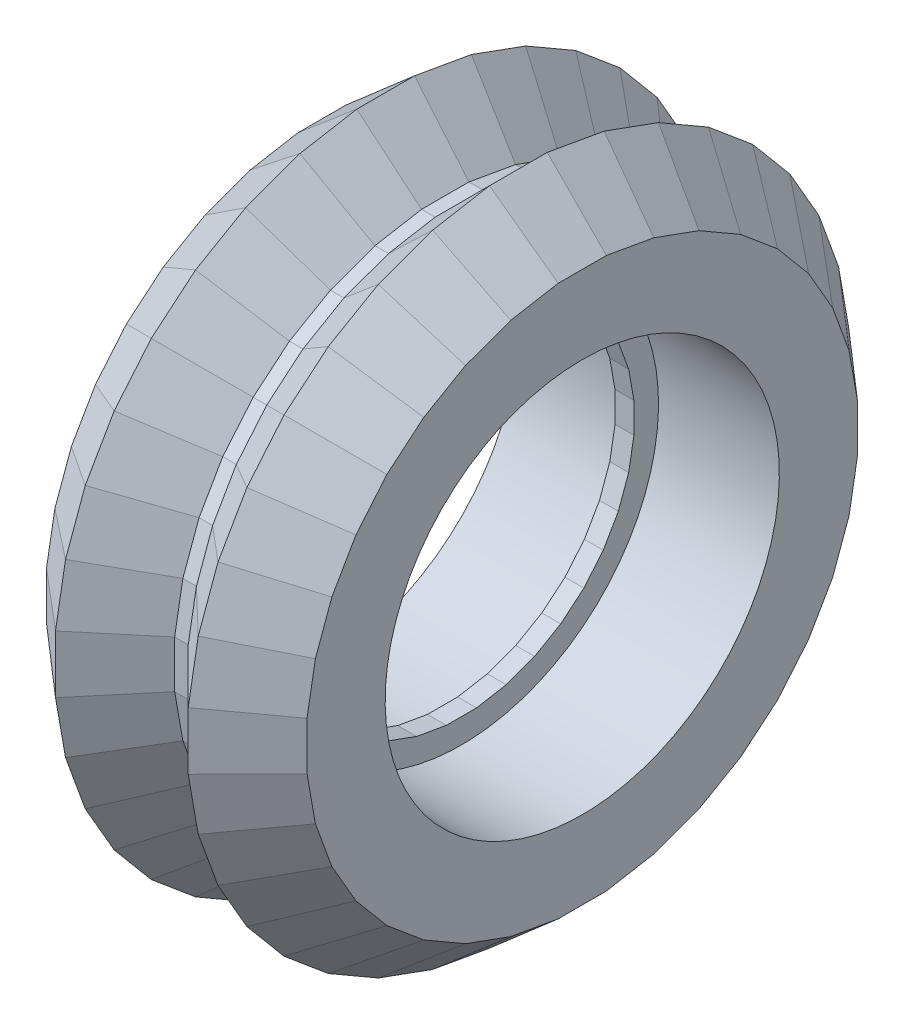
SolidWorks part; units mm, degrees
material "Chrome Stainless Steel"
ref_plane "Front Plane" through (0, 0, 0) normal (0, 0, 1) x (1, 0, 0)
ref_plane "Top Plane" through (0, 0, 0) normal (0, 1, 0) x (1, 0, 0)
ref_plane "Right Plane" through (0, 0, 0) normal (1, 0, 0) x (0, 0, -1)
sketch "Sketch1" plane through (0, 0, 0) normal (0, 0, 1) x (1, 0, 0)
  line L0 (-0.275, 10.9817) -> (0.275, 10.9817)
  line L1 (0.3833, 7) -> (0.3833, 7.5)
  line L2 (0.3833, 7.5) -> (5.0033, 7.5)
  line L3 (5.0033, 7.5) -> (5.2863, 7.783)
  line L4 (5.2863, 7.783) -> (5.2863, 11.17)
  line L5 (0.275, 10.9817) -> (2.6933, 13.4)
  line L6 (-0.3833, 7) -> (0.3833, 7)
  line L7 (-2.6933, 13.4) -> (-2.6933, 7.5) construction
  line L8 (-2.6933, 13.4) -> (-5.2863, 11.17)
  line L9 (2.6933, 13.4) -> (2.6933, 7.5) construction
  line L10 (0, 7) -> (0, 10.9817) construction
  line L11 (0, 7) -> (0, 0) construction
  line L12 (0, 0) -> (-5, 0) construction
  line L13 (-0.275, 10.9817) -> (-2.6933, 13.4)
  line L14 (-5.2863, 7.783) -> (-5.2863, 11.17)
  line L15 (2.6933, 13.4) -> (5.2863, 11.17)
  line L16 (-5.0033, 7.5) -> (-5.2863, 7.783)
  line L17 (-0.3833, 7.5) -> (-5.0033, 7.5)
  line L18 (-0.3833, 7) -> (-0.3833, 7.5)
  dimension "D2" = 90
  dimension "D3" = 3.42
  dimension "D4" = 7.5
  dimension "D5" = 0.275
  dimension "D6" = 4.62
  dimension "D7" = 135
  dimension "D8" = 0.4002
  dimension "D9" = 13.4
  dimension "D10" = 7
  dimension "D11" = 5
sketch "Sketch2" plane through (0, 0, 0) normal (1, 0, 0) x (0, 0, -1)
  line L0 (3.1177, -11.6354) -> (5.0908, -10.9172)
  line L1 (-8.5177, -8.5177) -> (-6.9092, -9.8674)
  line L2 (-6.9092, -9.8674) -> (-5.0908, -10.9172)
  line L3 (-5.0908, -10.9172) -> (-3.1177, -11.6354)
  line L4 (-3.1177, -11.6354) -> (-1.0499, -12)
  line L5 (-1.0499, -12) -> (1.0499, -12)
  line L6 (1.0499, -12) -> (3.1177, -11.6354)
  line L7 (5.0908, -10.9172) -> (6.9092, -9.8674)
  line L8 (6.9092, -9.8674) -> (8.5177, -8.5177)
  line L9 (8.5177, -8.5177) -> (9.8674, -6.9092)
  line L10 (9.8674, -6.9092) -> (10.9172, -5.0908)
  line L11 (10.9172, -5.0908) -> (11.6354, -3.1177)
  line L12 (11.6354, -3.1177) -> (12, -1.0499)
  line L13 (12, -1.0499) -> (12, 1.0499)
  line L14 (12, 1.0499) -> (11.6354, 3.1177)
  line L15 (11.6354, 3.1177) -> (10.9172, 5.0908)
  line L16 (10.9172, 5.0908) -> (9.8674, 6.9092)
  line L17 (9.8674, 6.9092) -> (8.5177, 8.5177)
  line L18 (8.5177, 8.5177) -> (6.9092, 9.8674)
  line L19 (6.9092, 9.8674) -> (5.0908, 10.9172)
  line L20 (5.0908, 10.9172) -> (3.1177, 11.6354)
  line L21 (3.1177, 11.6354) -> (1.0499, 12)
  line L22 (1.0499, 12) -> (-1.0499, 12)
  line L23 (-1.0499, 12) -> (-3.1177, 11.6354)
  line L24 (-3.1177, 11.6354) -> (-5.0908, 10.9172)
  line L25 (-5.0908, 10.9172) -> (-6.9092, 9.8674)
  line L26 (-6.9092, 9.8674) -> (-8.5177, 8.5177)
  line L27 (-8.5177, 8.5177) -> (-9.8674, 6.9092)
  line L28 (-9.8674, 6.9092) -> (-10.9172, 5.0908)
  line L29 (-10.9172, 5.0908) -> (-11.6354, 3.1177)
  line L30 (-11.6354, 3.1177) -> (-12, 1.0499)
  line L31 (-12, 1.0499) -> (-12, -1.0499)
  line L32 (-12, -1.0499) -> (-11.6354, -3.1177)
  line L33 (-11.6354, -3.1177) -> (-10.9172, -5.0908)
  line L34 (-10.9172, -5.0908) -> (-9.8674, -6.9092)
  line L35 (-9.8674, -6.9092) -> (-8.5177, -8.5177)
  circle A0 centre (0, 0) radius 12 construction
  dimension "D1" = 24
sweep "Sweep3" add profiles "Sketch1" path "Sketch2"
sketch "Sketch3" plane through (-0.3833, 0, 0) normal (-1, 0, 0) x (0, 0, 1)
  circle A0 centre (0, 0) radius 8
  dimension "D1" = 16
sketch "Sketch4" plane through (0.3833, 0, 0) normal (1, 0, 0) x (0, 0, -1)
  circle A0 centre (0, 0) radius 8
  dimension "D1" = 16
extrude "Cut-Extrude1" cut sketch "Sketch3" along normal blind 5
extrude "Cut-Extrude2" cut sketch "Sketch4" along normal blind 5
